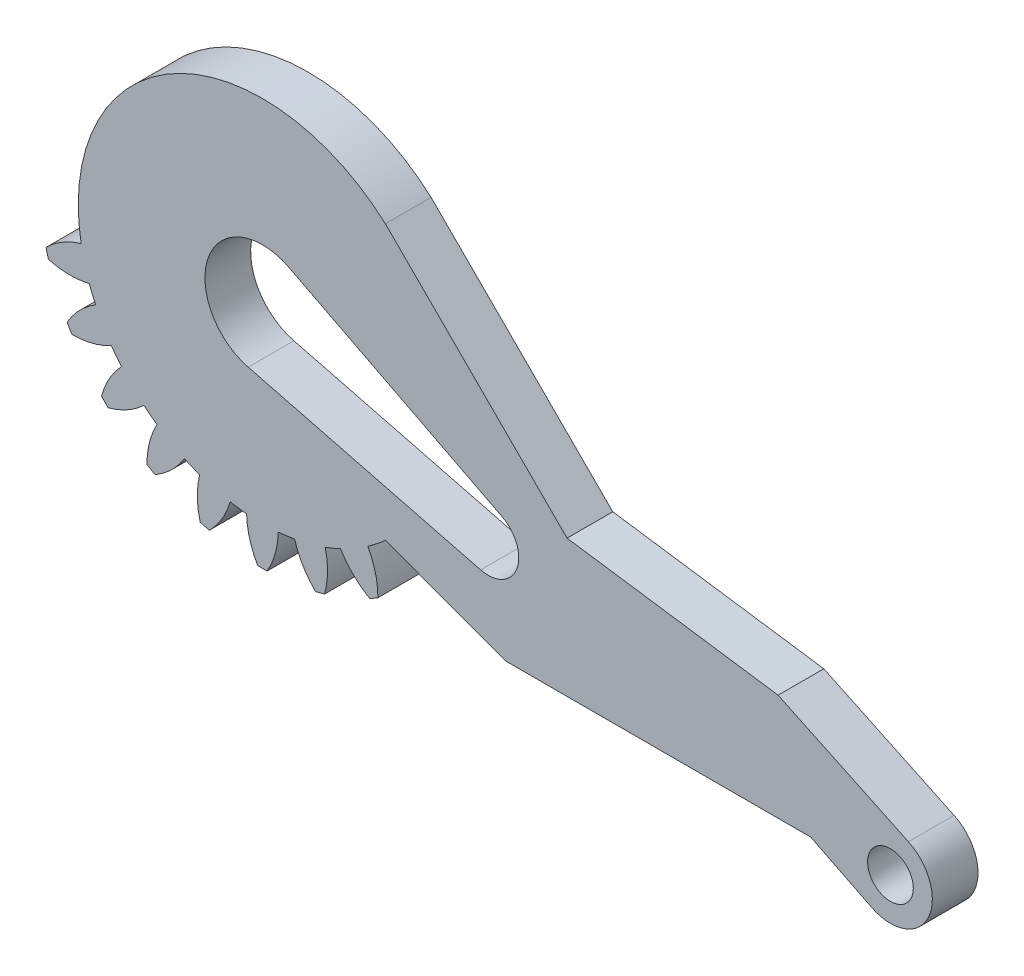
SolidWorks part; units mm, degrees
ref_plane "Front Plane" through (0, 0, 0) normal (0, 0, 1) x (1, 0, 0)
ref_plane "Top Plane" through (0, 0, 0) normal (0, 1, 0) x (1, 0, 0)
ref_plane "Right Plane" through (0, 0, 0) normal (1, 0, 0) x (0, 0, -1)
sketch "Sketch2" plane through (0, 0, 0) normal (0, 0, 1) x (1, 0, 0)
  line L0 (0, 0) -> (0, 14.63) construction
  line L1 (20, -2.9114) -> (33.8564, -4.9114)
  line L2 (8.0727, 9) -> (20, -2.9114)
  line L3 (16, -11.9114) -> (8.0727, -9)
  line L4 (33.8564, -4.9114) -> (42.4082, -8.9667)
  line L5 (16, -11.9114) -> (36, -11.9114)
  line L6 (36, -11.9114) -> (40, -13.9114)
  circle A0 centre (0, 0) radius 14.63
  circle A1 centre (0, 0) radius 12.09
  arc A3 (-0.31, 14.6267) -> (-1.04, 12.0452) centre (4.3584, 11.9126) ccw
  arc A4 (0.31, 14.6267) -> (1.04, 12.0452) centre (-4.3584, 11.9126) cw
  arc A5 (3.4862, 14.2086) -> (2.113, 11.9039) centre (7.2931, 10.3787) ccw
  arc A6 (4.0851, 14.0481) -> (4.1221, 11.3656) centre (-1.1267, 12.6347) cw
  arc A7 (7.0449, 12.8221) -> (5.1219, 10.9514) centre (9.7308, 8.1374) ccw
  arc A8 (7.5818, 12.5121) -> (6.9233, 9.9114) centre (2.1819, 12.4958) cw
  arc A9 (10.1234, 10.5619) -> (7.7818, 9.2526) centre (11.5053, 5.3417) ccw
  arc A10 (10.5619, 10.1234) -> (9.2526, 7.7818) centre (5.3417, 11.5053) cw
  arc A11 (12.5121, 7.5818) -> (9.9114, 6.9233) centre (12.4958, 2.1819) ccw
  arc A12 (12.8221, 7.0449) -> (10.9514, 5.1219) centre (8.1374, 9.7308) cw
  arc A13 (14.0481, 4.0851) -> (11.3656, 4.1221) centre (12.6347, -1.1267) ccw
  arc A14 (14.2086, 3.4862) -> (11.9039, 2.113) centre (10.3787, 7.2931) cw
  arc A15 (14.6267, 0.31) -> (12.0452, 1.04) centre (11.9126, -4.3584) ccw
  arc A16 (14.6267, -0.31) -> (12.0452, -1.04) centre (11.9126, 4.3584) cw
  arc A17 (14.2086, -3.4862) -> (11.9039, -2.113) centre (10.3787, -7.2931) ccw
  arc A18 (14.0481, -4.0851) -> (11.3656, -4.1221) centre (12.6347, 1.1267) cw
  arc A19 (12.8221, -7.0449) -> (10.9514, -5.1219) centre (8.1374, -9.7308) ccw
  arc A20 (12.5121, -7.5818) -> (9.9114, -6.9233) centre (12.4958, -2.1819) cw
  arc A21 (10.5619, -10.1234) -> (9.2526, -7.7818) centre (5.3417, -11.5053) ccw
  arc A22 (10.1234, -10.5619) -> (7.7818, -9.2526) centre (11.5053, -5.3417) cw
  arc A23 (7.5818, -12.5121) -> (6.9233, -9.9114) centre (2.1819, -12.4958) ccw
  arc A24 (7.0449, -12.8221) -> (5.1219, -10.9514) centre (9.7308, -8.1374) cw
  arc A25 (4.0851, -14.0481) -> (4.1221, -11.3656) centre (-1.1267, -12.6347) ccw
  arc A26 (3.4862, -14.2086) -> (2.113, -11.9039) centre (7.2931, -10.3787) cw
  arc A27 (0.31, -14.6267) -> (1.04, -12.0452) centre (-4.3584, -11.9126) ccw
  arc A28 (-0.31, -14.6267) -> (-1.04, -12.0452) centre (4.3584, -11.9126) cw
  arc A29 (-3.4862, -14.2086) -> (-2.113, -11.9039) centre (-7.2931, -10.3787) ccw
  arc A30 (-4.0851, -14.0481) -> (-4.1221, -11.3656) centre (1.1267, -12.6347) cw
  arc A31 (-7.0449, -12.8221) -> (-5.1219, -10.9514) centre (-9.7308, -8.1374) ccw
  arc A32 (-7.5818, -12.5121) -> (-6.9233, -9.9114) centre (-2.1819, -12.4958) cw
  arc A33 (-10.1234, -10.5619) -> (-7.7818, -9.2526) centre (-11.5053, -5.3417) ccw
  arc A34 (-10.5619, -10.1234) -> (-9.2526, -7.7818) centre (-5.3417, -11.5053) cw
  arc A35 (-12.5121, -7.5818) -> (-9.9114, -6.9233) centre (-12.4958, -2.1819) ccw
  arc A36 (-12.8221, -7.0449) -> (-10.9514, -5.1219) centre (-8.1374, -9.7308) cw
  arc A37 (-14.0481, -4.0851) -> (-11.3656, -4.1221) centre (-12.6347, 1.1267) ccw
  arc A38 (-14.2086, -3.4862) -> (-11.9039, -2.113) centre (-10.3787, -7.2931) cw
  arc A39 (-14.6267, -0.31) -> (-12.0452, -1.04) centre (-11.9126, 4.3584) ccw
  arc A40 (-14.6267, 0.31) -> (-12.0452, 1.04) centre (-11.9126, -4.3584) cw
  arc A41 (-14.2086, 3.4862) -> (-11.9039, 2.113) centre (-10.3787, 7.2931) ccw
  arc A42 (-14.0481, 4.0851) -> (-11.3656, 4.1221) centre (-12.6347, -1.1267) cw
  arc A43 (-12.8221, 7.0449) -> (-10.9514, 5.1219) centre (-8.1374, 9.7308) ccw
  arc A44 (-12.5121, 7.5818) -> (-9.9114, 6.9233) centre (-12.4958, 2.1819) cw
  arc A45 (-10.5619, 10.1234) -> (-9.2526, 7.7818) centre (-5.3417, 11.5053) ccw
  arc A46 (-10.1234, 10.5619) -> (-7.7818, 9.2526) centre (-11.5053, 5.3417) cw
  arc A47 (-7.5818, 12.5121) -> (-6.9233, 9.9114) centre (-2.1819, 12.4958) ccw
  arc A48 (-7.0449, 12.8221) -> (-5.1219, 10.9514) centre (-9.7308, 8.1374) cw
  arc A49 (-4.0851, 14.0481) -> (-4.1221, 11.3656) centre (1.1267, 12.6347) ccw
  arc A50 (-3.4862, 14.2086) -> (-2.113, 11.9039) centre (-7.2931, 10.3787) cw
  arc A51 (42.4082, -8.9667) -> (40, -13.9114) centre (41.2299, -11.4516) cw
  circle A52 centre (41.2299, -11.4516) radius 1.5
  point P154 (0, 0)
  dimension "D2" = 24.18
  dimension "D3" = 29.26
  dimension "D4" = 0.62
  dimension "D6" = 5.4
  dimension "D8" = 16
  dimension "D9" = 18
  dimension "D10" = 3
  dimension "D5" = 2.08
  dimension "D11" = 4
  dimension "D12" = 2
  dimension "D13" = 20
  dimension "D14" = 4
  dimension "D15" = 5.5
  dimension "D16" = 7
  dimension "D17" = 14
  dimension "D18" = 2
  dimension "D19" = 9
  dimension "D7" = 24
extrude "Boss-Extrude2" add sketch "Sketch2" along normal blind 3
sketch "Sketch4" plane through (0, 0, 0) normal (0, 0, -1) x (-1, 0, 0)
  line L0 (-1.7211, 3.3582) -> (-15.7376, -3.825)
  line L1 (0.9334, -3.6563) -> (-14.3272, -7.5521)
  arc A0 (-1.7211, 3.3582) -> (0.9334, -3.6563) centre (0, 0) cw
  arc A1 (-15.7376, -3.825) -> (-14.3272, -7.5521) centre (-14.8231, -5.6094) ccw
  dimension "D1" = 2.005
  dimension "D2" = 3.7736
  dimension "D3" = 15.75
extrude "Cut-Extrude2" cut sketch "Sketch4" against normal blind 3
